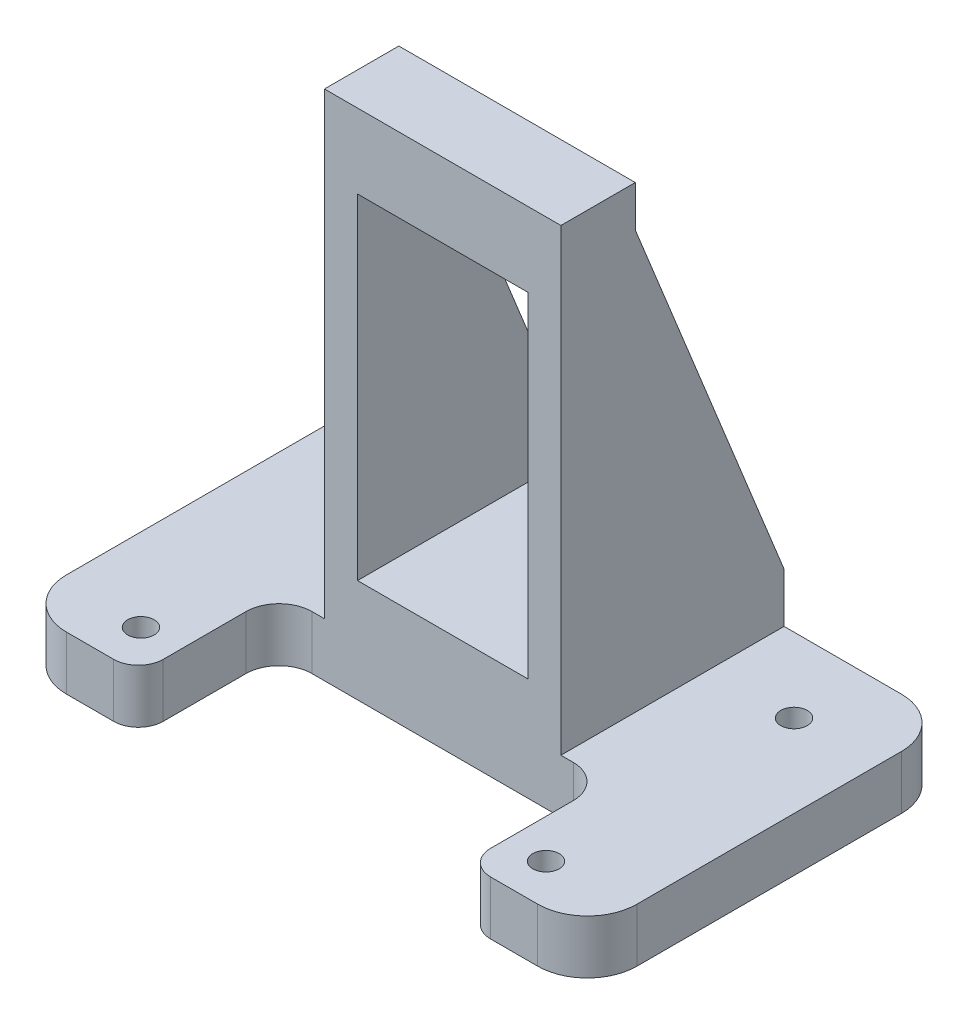
SolidWorks part; units mm, degrees
ref_plane "Front Plane" through (0, 0, 0) normal (0, 0, 1) x (1, 0, 0)
ref_plane "Top Plane" through (0, 0, 0) normal (0, 1, 0) x (1, 0, 0)
ref_plane "Right Plane" through (0, 0, 0) normal (1, 0, 0) x (0, 0, -1)
sketch "Sketch2" plane through (0, 0, 0) normal (0, 1, 0) x (1, 0, 0)
  line L0 (0, 42.444) -> (0, -11.1833) construction
  line L1 (-34.5, 39) -> (34.5, 39)
  line L2 (34.5, 39) -> (34.5, -5)
  line L3 (34.5, -5) -> (-34.5, -5)
  line L4 (-34.5, 39) -> (-34.5, -5)
  circle A0 centre (24.5, 30) radius 1.6
  circle A1 centre (24.5, 0) radius 1.6
  circle A2 centre (-24.5, 0) radius 1.6
  circle A3 centre (-24.5, 30) radius 1.6
  point P16 (0, -5)
  point P17 (0, 39)
  dimension "D3" = 3.2
  dimension "D4" = 3.2
  dimension "D1" = 24.5
  dimension "D2" = 30
  dimension "D5" = 34.5
  dimension "D6" = 9
  dimension "D7" = 5
extrude "Boss-Extrude1" add sketch "Sketch2" along normal blind 6.5
fillet "Fillet1" radius 6 4 edges at (34.5, 3.25, 5) (-34.5, 3.25, 5) (-34.5, 3.25, -39) (34.5, 3.25, -39)
sketch "Sketch3" plane through (0, 0, 5) normal (0, 0, 1) x (1, 0, 0)
  line L0 (0, -2.5336) -> (0, 69.8772) construction
  line L1 (-14.3, 6.5) -> (14.3, 6.5)
  line L2 (-28.5, 6.5) -> (28.5, 6.5) construction
  line L3 (14.3, 6.5) -> (14.3, 62)
  line L4 (14.3, 62) -> (-14.3, 62)
  line L5 (-10.3, 12.5) -> (10.3, 12.5)
  line L6 (10.3, 12.5) -> (10.3, 53)
  line L7 (10.3, 53) -> (-10.3, 53)
  line L8 (-28.5, 0) -> (28.5, 0) construction
  line L9 (-28.6843, 32.75) -> (24.1536, 32.75) construction
  line L10 (28.6843, 32.75) -> (-24.1536, 32.75) construction
  line L11 (-10.3, 12.5) -> (-10.3, 53)
  line L12 (-14.3, 6.5) -> (-14.3, 62)
  point P17 (10.3, 32.75)
  point P21 (0, 53)
  point P22 (0, 12.5)
  point P23 (0, 62)
  point P24 (0, 6.5)
  dimension "D1" = 12.5
  dimension "D2" = 40.5
  dimension "D3" = 9
  dimension "D4" = 4
  dimension "D5" = 10.3
extrude "Boss-Extrude2" add sketch "Sketch3" against normal up to surface (44 mm away) up to face at (0, 3.25, -39)
sketch "Sketch4" plane through (0, 0, 0) normal (1, 0, 0) x (0, 0, -1)
  line L0 (21, 62) -> (21, 57.0197)
  line L1 (39, 62) -> (-5, 62) construction
  line L2 (21, 57.0197) -> (39, 12.5)
  line L5 (39, 12.5) -> (39, 62)
  line L6 (39, 62) -> (21, 62)
  dimension "D1" = 18
extrude "Cut-Extrude1" cut sketch "Sketch4" against normal up to next and the other way up to next
sketch "Sketch5" plane through (0, 0, 5) normal (0, 0, 1) x (1, 0, 0)
  line L0 (-19.8, 62) -> (-19.8, 0)
  line L1 (-28.5, 0) -> (28.5, 0) construction
  line L2 (-19.8, 0) -> (19.8, 0)
  line L3 (19.8, 0) -> (19.8, 62)
  line L4 (19.8, 62) -> (-19.8, 62)
  line L5 (14.3, 62) -> (-14.3, 62) construction
  line L6 (-14.3, 62) -> (-14.3, 6.5) construction
  point P6 (0, 0)
  dimension "D1" = 5.5
extrude "Cut-Extrude2" cut sketch "Sketch5" against normal blind 17
fillet "Fillet2" radius 3 2 edges at (19.8, 3.25, 5) (-19.8, 3.25, 5)
fillet "Fillet3" radius 4 2 edges at (19.8, 3.25, -12) (-19.8, 3.25, -12)
sketch "Sketch6" plane through (0, 0, -39) normal (0, 0, -1) x (-1, 0, 0)
  text T0 "<r270>爱德智能车队</r>" font "@方正等线" height 3.5
extrude "Cut-Extrude5" cut sketch "Sketch6" against normal blind 5
